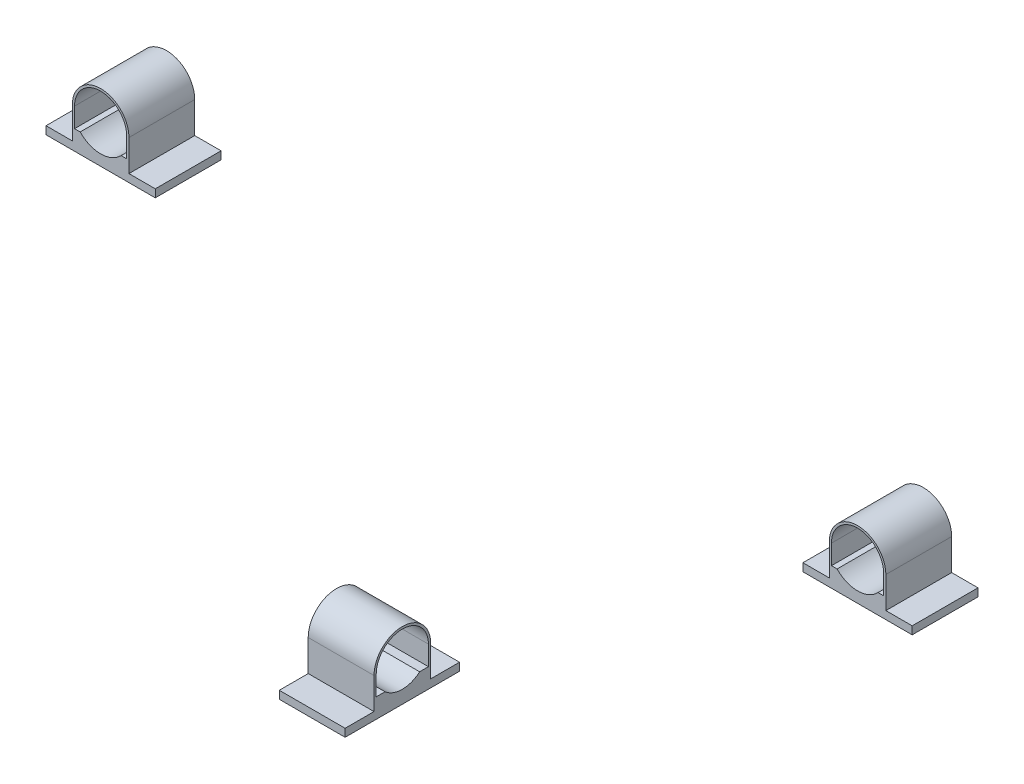
SolidWorks part; units mm, degrees
ref_plane "Front Plane" through (0, 0, 0) normal (0, 0, 1) x (1, 0, 0)
ref_plane "Top Plane" through (0, 0, 0) normal (0, 1, 0) x (1, 0, 0)
ref_plane "Right Plane" through (0, 0, 0) normal (1, 0, 0) x (0, 0, -1)
sketch "Sketch3" plane through (0, 0, 0) normal (0, 0, 1) x (1, 0, 0)
  line L0 (32.7671, -22.6228) -> (63.2587, -22.6228)
  line L1 (-32.7671, -22.6228) -> (32.7671, -22.6228)
  line L2 (-32.7671, -13.5245) -> (-32.7671, 22.6228)
  line L3 (63.2587, -22.6228) -> (63.2587, -13.5245)
  line L4 (32.7671, -13.5245) -> (32.7671, 22.6228)
  line L5 (63.2587, -13.5245) -> (32.7671, -13.5245)
  line L6 (0, 0) -> (0, 22.6228) construction
  line L7 (-32.7671, -22.6228) -> (-63.2587, -22.6228)
  line L8 (-63.2587, -22.6228) -> (-63.2587, -13.5245)
  line L9 (-63.2587, -13.5245) -> (-32.7671, -13.5245)
  line L10 (-30.2271, 0) -> (-23.7043, 0)
  line L11 (23.7043, 0) -> (30.2271, 0)
  line L12 (-30.2271, 22.6228) -> (-30.2271, 0)
  line L13 (30.2271, 22.6228) -> (30.2271, 0)
  line L14 (-909.1699, -22.6228) -> (-939.6615, -22.6228)
  line L15 (-876.4028, 0) -> (-876.4028, 22.6228) construction
  line L16 (-909.1699, -13.5245) -> (-909.1699, 22.6228)
  line L17 (-852.6985, 0) -> (-846.1757, 0)
  line L18 (-909.1699, -22.6228) -> (-843.6357, -22.6228)
  line L19 (-813.1441, -13.5245) -> (-843.6357, -13.5245)
  line L20 (-843.6357, -22.6228) -> (-813.1441, -22.6228)
  line L21 (-843.6357, -13.5245) -> (-843.6357, 22.6228)
  line L22 (-906.6299, 0) -> (-900.1071, 0)
  line L23 (-939.6615, -13.5245) -> (-909.1699, -13.5245)
  line L24 (-906.6299, 22.6228) -> (-906.6299, 0)
  line L25 (-939.6615, -22.6228) -> (-939.6615, -13.5245)
  line L26 (-846.1757, 22.6228) -> (-846.1757, 0)
  line L27 (-813.1441, -22.6228) -> (-813.1441, -13.5245)
  arc A0 (32.7671, 22.6228) -> (-32.7671, 22.6228) centre (0, 22.6228) ccw
  arc A1 (-23.7043, 0) -> (23.7043, 0) centre (0, 22.6228) ccw
  arc A2 (30.2271, 22.6228) -> (-30.2271, 22.6228) centre (0, 22.6228) ccw
  arc A3 (-843.6357, 22.6228) -> (-909.1699, 22.6228) centre (-876.4028, 22.6228) ccw
  arc A4 (-900.1071, 0) -> (-852.6985, 0) centre (-876.4028, 22.6228) ccw
  arc A5 (-846.1757, 22.6228) -> (-906.6299, 22.6228) centre (-876.4028, 22.6228) ccw
  point P0 (0, 0)
  point P16 (-876.4028, 0)
  dimension "D2" = 32.7671
  dimension "D3" = 45.2456
  dimension "D4" = 126.5174
  dimension "D5" = 22.6228
  dimension "D6" = 9.0983
  dimension "D1" = 2.54
ref_plane "Plane1" through (0, 0, 203.2) normal (0, 0, 1) x (1, 0, 0)
sketch "Sketch1" plane through (0, 0, 203.2) normal (0, 0, 1) x (1, 0, 0)
  line L0 (-876.4028, 22.6228) -> (0, 22.6228) construction
  line L1 (-438.2014, 22.6228) -> (-438.2014, -215.9399) construction
ref_plane "Plane2" through (-438.2014, 0, 0) normal (-1, 0, 0) x (0, 0, 1)
sketch "Sketch4" plane through (-438.2014, 0, 0) normal (-1, 0, 0) x (0, 0, 1)
  line L0 (233.426, -237.8046) -> (223.2357, -237.8046)
  line L1 (170.434, -215.1732) -> (170.434, -237.8046)
  line L2 (235.966, -215.1732) -> (235.966, -237.8046)
  line L3 (172.974, -215.1732) -> (172.974, -237.8046)
  line L4 (233.426, -215.1732) -> (233.426, -237.8046)
  line L5 (170.434, -237.8046) -> (170.434, -251.3174)
  line L6 (170.434, -251.3174) -> (136.9624, -251.3174)
  line L7 (136.9624, -251.3174) -> (136.9624, -260.4106)
  line L8 (136.9624, -260.4106) -> (269.4376, -260.4106)
  line L9 (203.2, -215.1732) -> (203.2, -219.0716) construction
  line L10 (269.4376, -251.3174) -> (269.4376, -260.4106)
  line L11 (235.966, -251.3174) -> (269.4376, -251.3174)
  line L12 (235.966, -237.8046) -> (235.966, -251.3174)
  line L13 (183.1643, -237.8046) -> (172.974, -237.8046)
  arc A0 (233.426, -215.1732) -> (172.974, -215.1732) centre (203.2, -215.1732) ccw
  arc A1 (235.966, -215.1732) -> (170.434, -215.1732) centre (203.2, -215.1732) ccw
  arc A2 (233.426, -215.1732) -> (172.974, -215.1732) centre (203.2, -215.1732) ccw
  arc A3 (183.1643, -237.8046) -> (223.2357, -237.8046) centre (203.2, -215.1732) ccw
  point P17 (203.2, -260.4106)
  dimension "D1" = 65.532
  dimension "D2" = 22.6314
  dimension "D5" = 45.2374
  dimension "D6" = 9.0932
  dimension "D3" = 2.54
  dimension "D4" = 2.54
ref_plane "Plane3" through (0, 0, 76.2) normal (0, 0, 1) x (1, 0, 0)
sketch "Sketch2" plane through (0, 0, 0) normal (0, 0, 1) x (1, 0, 0)
  circle A0 centre (0, 22.6228) radius 30.2271
extrude "Extrude1" add sketch "Sketch3" along normal blind 76.2
extrude "Extrude2" add sketch "Sketch4" along normal mid plane 76.2 contours L2 A1 L1 L5 L6 L7 L8 L10 L11 L12 A3 L13 L3 A0 L4 L0
sketch3d "3DSketch2"
  line L0 (0, 22.6228, 0) -> (0, 22.6228, 76.2) construction
  line L1 (0, 22.6228, 76.2) -> (0, 22.6228, 0) construction
  line L2 (-876.4028, 22.0522, 0) -> (-876.4028, 22.6228, 76.2) construction
  line L3 (-876.4028, 0, 0) -> (-876.4028, 22.6228, 0) construction
  line L4 (-876.4028, 22.6228, 76.2) -> (-876.4028, 22.6228, 0) construction
  line L5 (-400.1014, -215.1732, 203.2) -> (-476.3014, -215.1732, 203.2) construction
  line L6 (-476.3014, -215.1732, 203.2) -> (-400.1014, -215.1732, 203.2) construction
  line L7 (-476.3014, -215.1732, 203.2) -> (-400.1014, -215.1732, 203.2) construction
sketch "Sketch5" plane through (0, 0, 0) normal (0, 0, 1) x (1, 0, 0)
  circle A0 centre (0, 22.6228) radius 30.1625
curve "Curve2"
